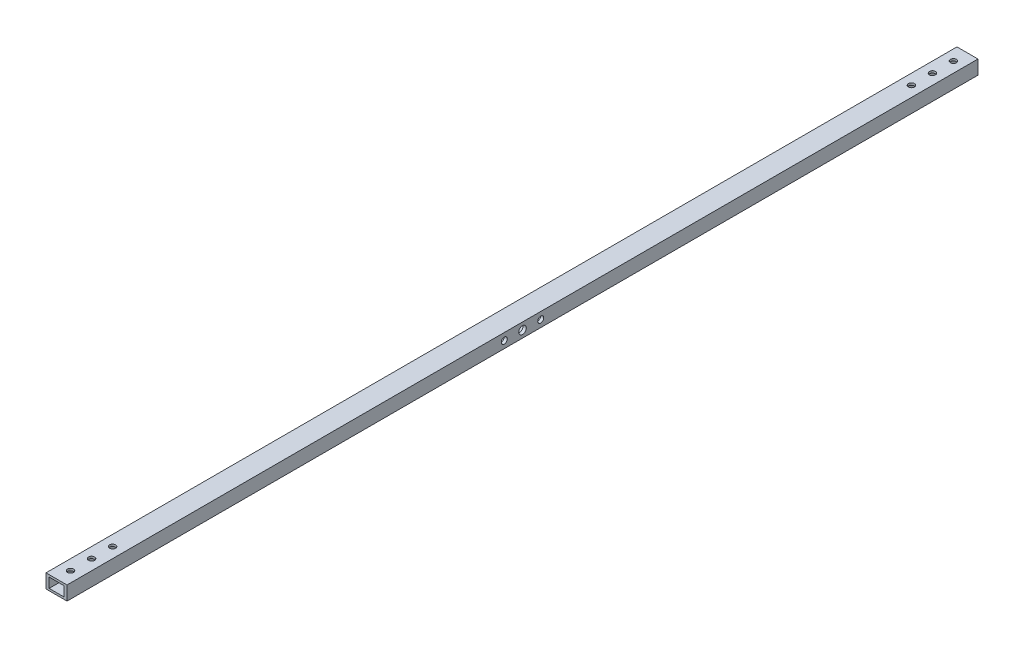
SolidWorks part; units mm, degrees
material "PC 高粘度"
ref_plane "前视基准面" through (0, 0, 0) normal (0, 0, 1) x (1, 0, 0)
ref_plane "上视基准面" through (0, 0, 0) normal (0, 1, 0) x (1, 0, 0)
ref_plane "右视基准面" through (0, 0, 0) normal (1, 0, 0) x (0, 0, -1)
other "Configuration Table"
sketch "草图1" plane through (0, 0, 0) normal (0, 0, 1) x (1, 0, 0)
  line L1 (-7.5, 5) -> (7.5, 5)
  line L2 (-7.5, 5) -> (-7.5, -5)
  line L3 (-7.5, -5) -> (7.5, -5)
  line L4 (7.5, 5) -> (7.5, -5)
  line L5 (-7.5, 5) -> (7.5, -5) construction
  line L6 (-7.5, -5) -> (7.5, 5) construction
  line L7 (-5.25, 3.5) -> (5.25, 3.5)
  line L8 (-5.25, 3.5) -> (-5.25, -3.5)
  line L9 (-5.25, -3.5) -> (5.25, -3.5)
  line L10 (5.25, 3.5) -> (5.25, -3.5)
  line L11 (-5.25, 3.5) -> (5.25, -3.5) construction
  line L12 (-5.25, -3.5) -> (5.25, 3.5) construction
  point P0 (0, 0)
  point P5 (0, 0)
  dimension "D1" = 10
  dimension "D2" = 1.5
  dimension "D3" = 15
extrude "凸台-拉伸1" add sketch "草图1" along normal blind 650
sketch "草图2" plane through (0, -5, 0) normal (0, -1, 0) x (1, 0, 0)
  line L4 (-7.5, 0) -> (7.5, 0)
  line L5 (7.5, 0) -> (7.5, 650)
  line L6 (7.5, 650) -> (-7.5, 650)
  line L7 (-7.5, 650) -> (-7.5, 0)
  line L8 (-7.5, 0) -> (7.5, 0)
  line L9 (7.5, 0) -> (7.5, 650)
  line L10 (7.5, 650) -> (-7.5, 650)
  line L11 (-7.5, 650) -> (-7.5, 0)
  circle A0 centre (0, 640) radius 2.15 construction
  circle A1 centre (0, 625) radius 2.15 construction
  circle A2 centre (0, 610) radius 2.15 construction
  circle A3 centre (0, 40) radius 2.15 construction
  circle A4 centre (0, 25) radius 2.15 construction
  circle A5 centre (0, 10) radius 2.15 construction
  circle A6 centre (0, 640) radius 2.15
  circle A7 centre (0, 625) radius 2.15
  circle A8 centre (0, 610) radius 2.15
  circle A9 centre (0, 40) radius 2.15
  circle A10 centre (0, 25) radius 2.15
  circle A11 centre (0, 10) radius 2.15
  dimension "D1" = 0
extrude "切除-拉伸1" cut sketch "草图2" against normal through all contours A6 | A7 | A8 | A11 | A10 | A9
sketch "草图3" plane through (7.5, 0, 0) normal (1, 0, 0) x (0, 0, -1)
  circle A0 centre (-338, 0) radius 2.15 construction
  circle A1 centre (-312, 0) radius 2.15 construction
  circle A2 centre (-338, 0) radius 2.15
  circle A3 centre (-312, 0) radius 2.15
  circle A4 centre (-325, 0) radius 2.7 construction
  circle A5 centre (-325, 0) radius 2.7
extrude "切除-拉伸2" cut sketch "草图3" against normal through all
